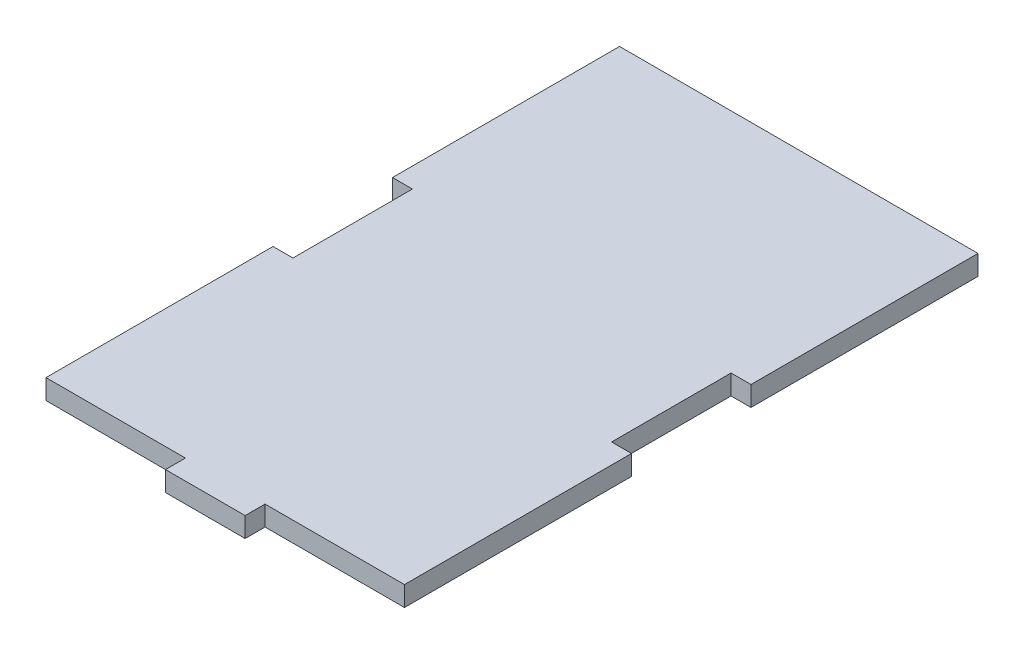
SolidWorks part; units mm, degrees
ref_plane "Front Plane" through (0, 0, 0) normal (0, 0, 1) x (1, 0, 0)
ref_plane "Top Plane" through (0, 0, 0) normal (0, 1, 0) x (1, 0, 0)
ref_plane "Right Plane" through (0, 0, 0) normal (1, 0, 0) x (0, 0, -1)
sketch "Sketch1" plane through (0, 0, 0) normal (0, 1, 0) x (1, 0, 0)
  line L1 (-45, 72) -> (45, 72)
  line L2 (-45, 72) -> (-45, 15)
  line L3 (-45, -72) -> (-10, -72)
  line L4 (45, 72) -> (45, 15)
  line L5 (-45, 72) -> (45, -72) construction
  line L6 (-45, -72) -> (45, 72) construction
  line L8 (-10, -72) -> (-10, -67)
  line L10 (10, -67) -> (10, -72)
  line L11 (10, -72) -> (45, -72)
  line L14 (45, 15) -> (40, 15)
  line L15 (40, 15) -> (40, -15)
  line L16 (40, -15) -> (45, -15)
  line L17 (0, -55) -> (0, 55) construction
  line L18 (-40, 15) -> (-40, -15)
  line L19 (-45, 15) -> (-40, 15)
  line L20 (-40, -15) -> (-45, -15)
  line L21 (45, -15) -> (45, -72)
  line L22 (-45, -15) -> (-45, -72)
  line L24 (10, -72) -> (10, -77)
  line L25 (10, -77) -> (-10, -77)
  line L26 (-10, -77) -> (-10, -72)
  point P0 (0, 0)
  dimension "D1" = 144
  dimension "D2" = 90
  dimension "D3" = 5
  dimension "D5" = 5
  dimension "D6" = 5
extrude "Boss-Extrude1" add sketch "Sketch1" along normal blind 5
